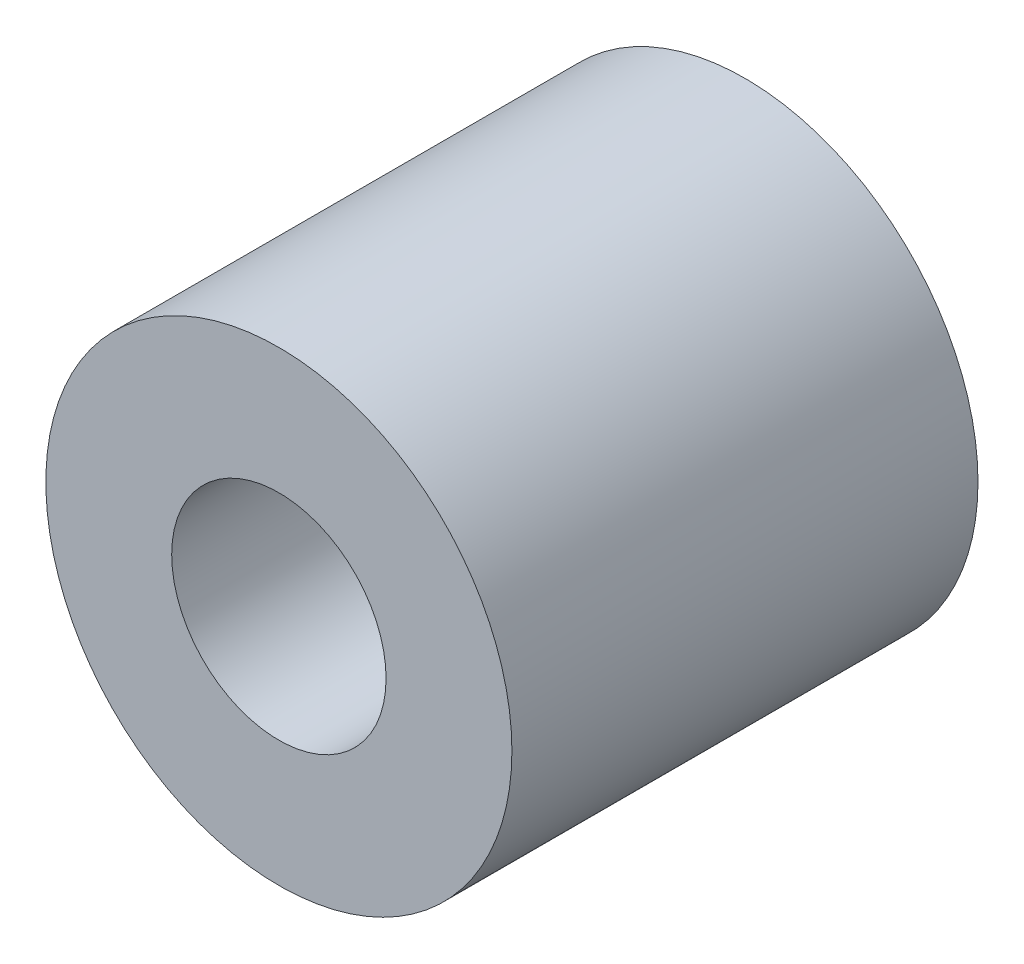
SolidWorks part; units mm, degrees
material "6061-T6 (SS)"
ref_plane "Front Plane" through (0, 0, 0) normal (0, 0, 1) x (1, 0, 0)
ref_plane "Top Plane" through (0, 0, 0) normal (0, 1, 0) x (1, 0, 0)
ref_plane "Right Plane" through (0, 0, 0) normal (1, 0, 0) x (0, 0, -1)
sketch "Sketch1" plane through (0, 0, 0) normal (0, 0, 1) x (1, 0, 0)
  circle A0 centre (0, 0) radius 3.175
  circle A1 centre (0, 0) radius 1.4605
  dimension "OD" = 6.35
  dimension "ID" = 2.921
extrude "Extrude1" add sketch "Sketch1" along normal mid plane 6.35
sketch "Sketch2" plane through (0, 0, 0) normal (1, 0, 0) x (0, 0, -1)
  line L0 (-3.175, -1.4605) -> (3.175, -1.4605) construction
  line L3 (3.175, 1.4605) -> (-3.175, 1.4605) construction
  line L5 (-3.175, -1.4605) -> (3.175, -1.4605)
  line L6 (3.175, 1.4605) -> (-3.175, 1.4605)
sketch "Sketch4" plane through (0, 0, 3.175) normal (0, 0, 1) x (1, 0, 0)
  line L0 (0, 0) -> (-1.0327, 1.0327)
  line L1 (0, -2.1828) -> (0, 2.1828) construction
  circle A0 centre (0, 0) radius 1.4605 construction
  dimension "D1" = 45
